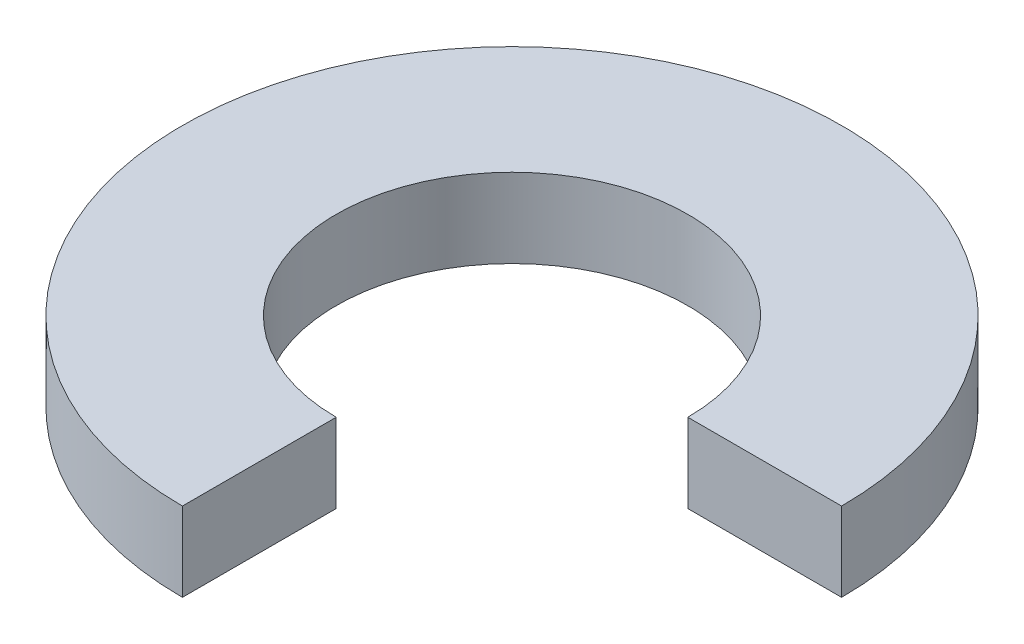
SolidWorks part; units mm, degrees
ref_plane "Alzado" through (0, 0, 0) normal (0, 0, 1) x (1, 0, 0)
ref_plane "Planta" through (0, 0, 0) normal (0, 1, 0) x (1, 0, 0)
ref_plane "Vista lateral" through (0, 0, 0) normal (1, 0, 0) x (0, 0, -1)
sketch "Croquis1" plane through (0, 0, 0) normal (0, 1, 0) x (1, 0, 0)
  line L0 (2, 0) -> (3.75, 0)
  line L1 (0, -2) -> (0, -3.75)
  arc A0 (2, 0) -> (0, -2) centre (0, 0) ccw
  arc A1 (3.75, 0) -> (0, -3.75) centre (0, 0) ccw
  dimension "D1" = 4
  dimension "D2" = 7.5
  dimension "D3" = 90
extrude "Saliente-Extruir1" add sketch "Croquis1" along normal blind 0.9
